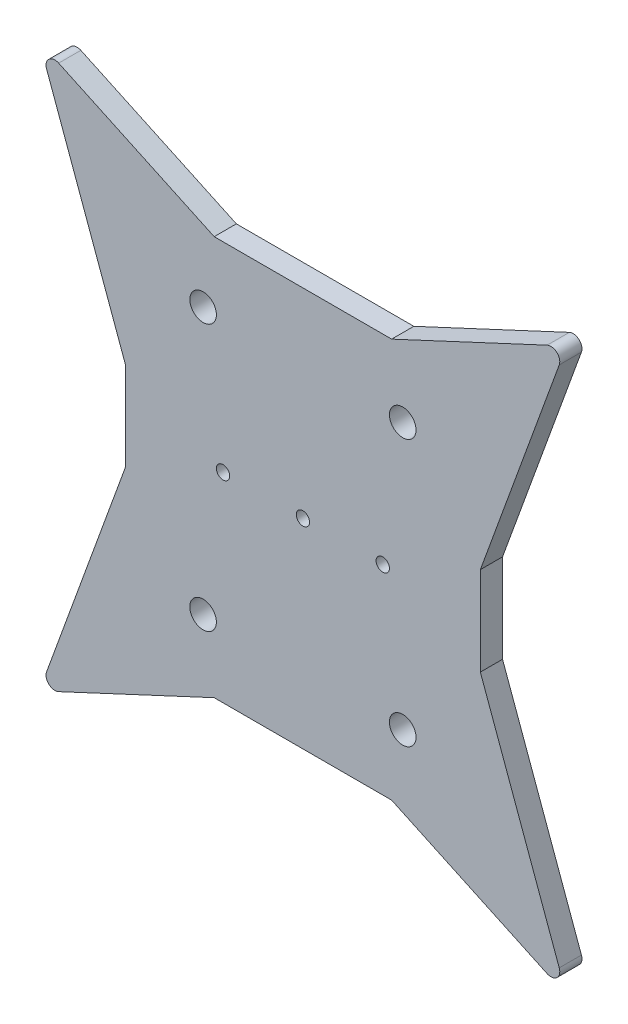
SolidWorks part; units mm, degrees
ref_plane "Front Plane" through (0, 0, 0) normal (0, 0, 1) x (1, 0, 0)
ref_plane "Top Plane" through (0, 0, 0) normal (0, 1, 0) x (1, 0, 0)
ref_plane "Right Plane" through (0, 0, 0) normal (1, 0, 0) x (0, 0, -1)
sketch "Sketch1" plane through (0, 0, 0) normal (0, 0, 1) x (1, 0, 0)
  line L0 (-78.5343, 0) -> (109.9735, 0) construction
  line L1 (0, 64.3489) -> (0, -95.298) construction
  line L3 (-20, 45) -> (20, 45)
  line L4 (20, 45) -> (59.4313, 63.3871)
  line L5 (59.4313, 63.3871) -> (40, 10)
  line L6 (40, 10) -> (40, -10)
  line L8 (-40, 10) -> (-40, -10)
  line L9 (-59.4313, 63.3871) -> (-40, 10)
  line L10 (-20, 45) -> (-59.4313, 63.3871)
  line L11 (-12.5, 41.4696) -> (-12.5, -40.5511) construction
  line L12 (12.5, 41.4696) -> (12.5, -40.5511) construction
  line L15 (-59.4313, -63.3871) -> (-40, -10)
  line L16 (-20, -45) -> (-59.4313, -63.3871)
  line L17 (-20, -45) -> (20, -45)
  line L18 (20, -45) -> (59.4313, -63.3871)
  line L19 (59.4313, -63.3871) -> (40, -10)
  circle A0 centre (-22.5, 30) radius 10 construction
  circle A1 centre (-22.5, 30) radius 9.5 construction
  circle A2 centre (-22.5, 30) radius 3
  circle A6 centre (0, 0) radius 1.5
  circle A7 centre (-18, 0) radius 1.5
  circle A8 centre (18, 0) radius 1.5
  circle A9 centre (22.5, 30) radius 3
  circle A10 centre (22.5, -30) radius 3
  circle A11 centre (-22.5, -30) radius 3
  circle A12 centre (22.5, 30) radius 10 construction
  circle A13 centre (22.5, -30) radius 10 construction
  circle A14 centre (-22.5, -30) radius 10 construction
  point P6 (0, 45)
  point P26 (-40, 0)
  point P31 (40, 0)
  point P39 (0, 0)
  point P40 (0, 0)
  point P51 (0, 5)
  dimension "D5" = 160
  dimension "D6" = 155
  dimension "D7" = 12.5
  dimension "D9" = 20
  dimension "D10" = 19
  dimension "D11" = 6
  dimension "D12" = 3
  dimension "D13" = 18
  dimension "D15" = 20
  dimension "D1" = 40
  dimension "D2" = 80
  dimension "D3" = 45
  dimension "D4" = 10
  dimension "D14" = 18
  dimension "D16" = 15
  dimension "D8" = 15
extrude "Boss-Extrude1" add sketch "Sketch1" along normal blind 5
fillet "Fillet1" radius 2 4 edges at (-59.4313, -63.3871, 2.5) (59.4313, -63.3871, 2.5) (59.4313, 63.3871, 2.5) (-59.4313, 63.3871, 2.5)
